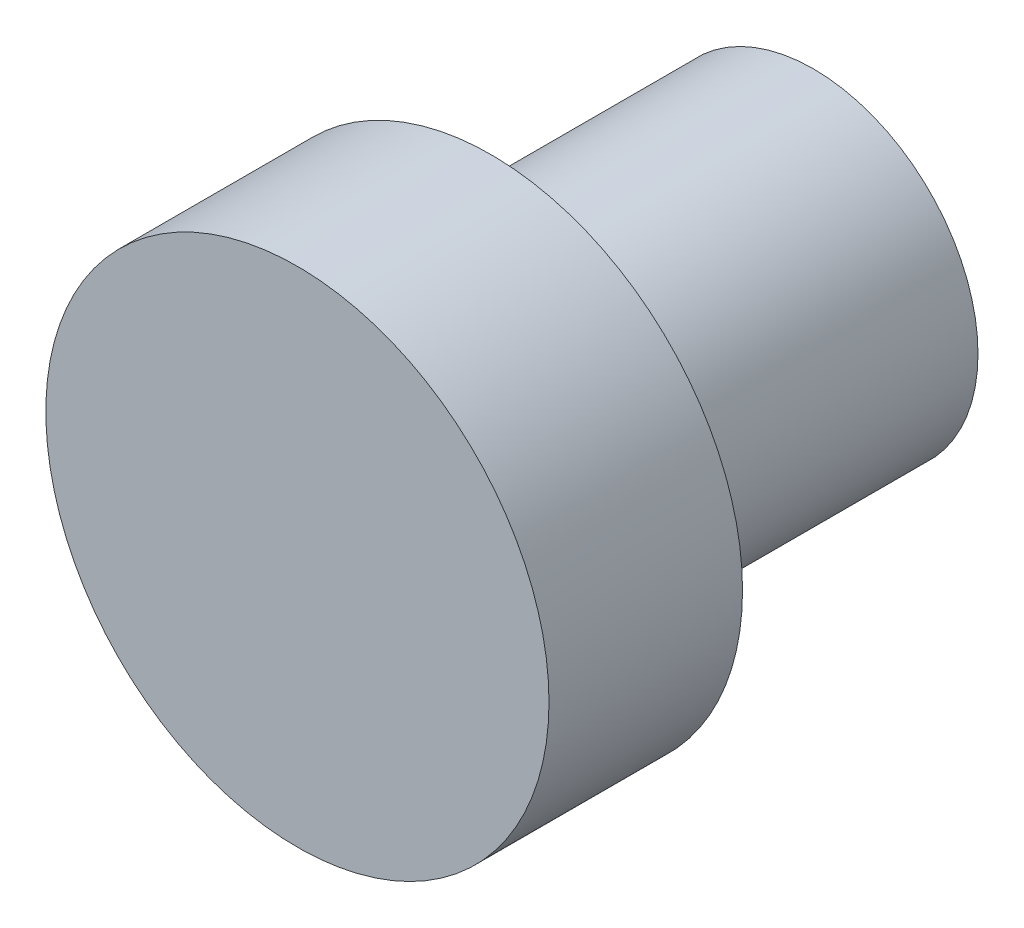
SolidWorks part; units mm, degrees
ref_plane "Ebene vorne" through (0, 0, 0) normal (0, 0, 1) x (1, 0, 0)
ref_plane "Ebene oben" through (0, 0, 0) normal (0, 1, 0) x (1, 0, 0)
ref_plane "Ebene rechts" through (0, 0, 0) normal (1, 0, 0) x (0, 0, -1)
sketch "Skizze1" plane through (0, 0, 0) normal (0, 0, 1) x (1, 0, 0)
  circle A0 centre (0, 0) radius 2.55
  dimension "D1" = 5.1
extrude "Aufsatz-Linear austragen1" add sketch "Skizze1" along normal blind 8
sketch "Skizze2" plane through (0, 0, 8) normal (0, 0, 1) x (1, 0, 0)
  circle A0 centre (0, 0) radius 3.9
  dimension "D1" = 7.8
extrude "Aufsatz-Linear austragen2" add sketch "Skizze2" against normal blind 3
sketch "Skizze3" plane through (0, 0, 0) normal (0, 0, -1) x (-1, 0, 0)
  circle A0 centre (0, 0) radius 2.25
  dimension "D1" = 4.5
